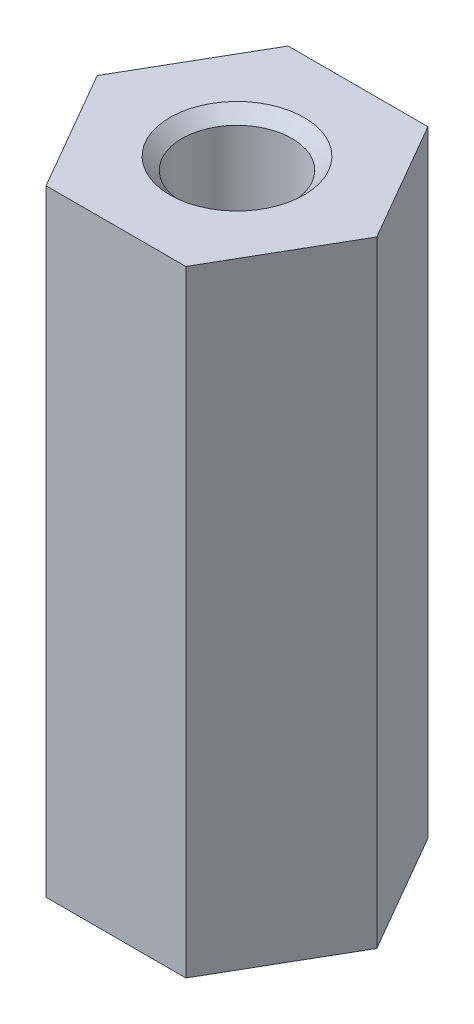
SolidWorks part; units mm, degrees
ref_plane "Ebene vorne" through (0, 0, 0) normal (0, 0, 1) x (1, 0, 0)
ref_plane "Ebene oben" through (0, 0, 0) normal (0, 1, 0) x (1, 0, 0)
ref_plane "Ebene rechts" through (0, 0, 0) normal (1, 0, 0) x (0, 0, -1)
sketch "Skizze1" plane through (0, 0, 0) normal (0, 1, 0) x (1, 0, 0)
  line L1 (3.1754, 0) -> (1.5877, 2.75)
  line L2 (1.5877, 2.75) -> (-1.5877, 2.75)
  line L3 (-1.5877, 2.75) -> (-3.1754, 0)
  line L4 (-3.1754, 0) -> (-1.5877, -2.75)
  line L5 (-1.5877, -2.75) -> (1.5877, -2.75)
  line L6 (1.5877, -2.75) -> (3.1754, 0)
  circle A0 centre (0, 0) radius 2.75 construction
  dimension "D1" = 5.5
extrude "Aufsatz-Linear austragen1" add sketch "Skizze1" along normal blind 14
hole_wizard "M3 Gewindebohrung1" positions "Skizze2" profile "Skizze3" tap size "M3" standard "DIN" end condition through all
sketch "Skizze2" plane through (0, 14, 0) normal (0, 1, 0) x (1, 0, 0)
  point P0 (0, 0)
cosmetic thread "Bohrungsgewinde1"
sketch "Skizze3" plane through (0, 14, 0) normal (1, 0, 0) x (0, 0, 1)
  line L0 (0, 0) -> (0, 14)
  line L1 (0, 14) -> (1.25, 14)
  line L2 (1.25, 14) -> (1.25, 0.275)
  line L3 (1.25, 0.275) -> (1.525, 0)
  line L5 (1.525, 0) -> (0, 0)
  line L6 (-1.25, 0.275) -> (-1.525, 0) construction
  line L11 (0, -6.35) -> (0, 107.95) construction
  dimension "Bohrerdurchmesser" = 2.5
  dimension "Bohrungstiefe" = 14
  dimension "Senkdurchmesser (Oben)" = 3.05
  dimension "Senkwinkel (Oben)" = 90
